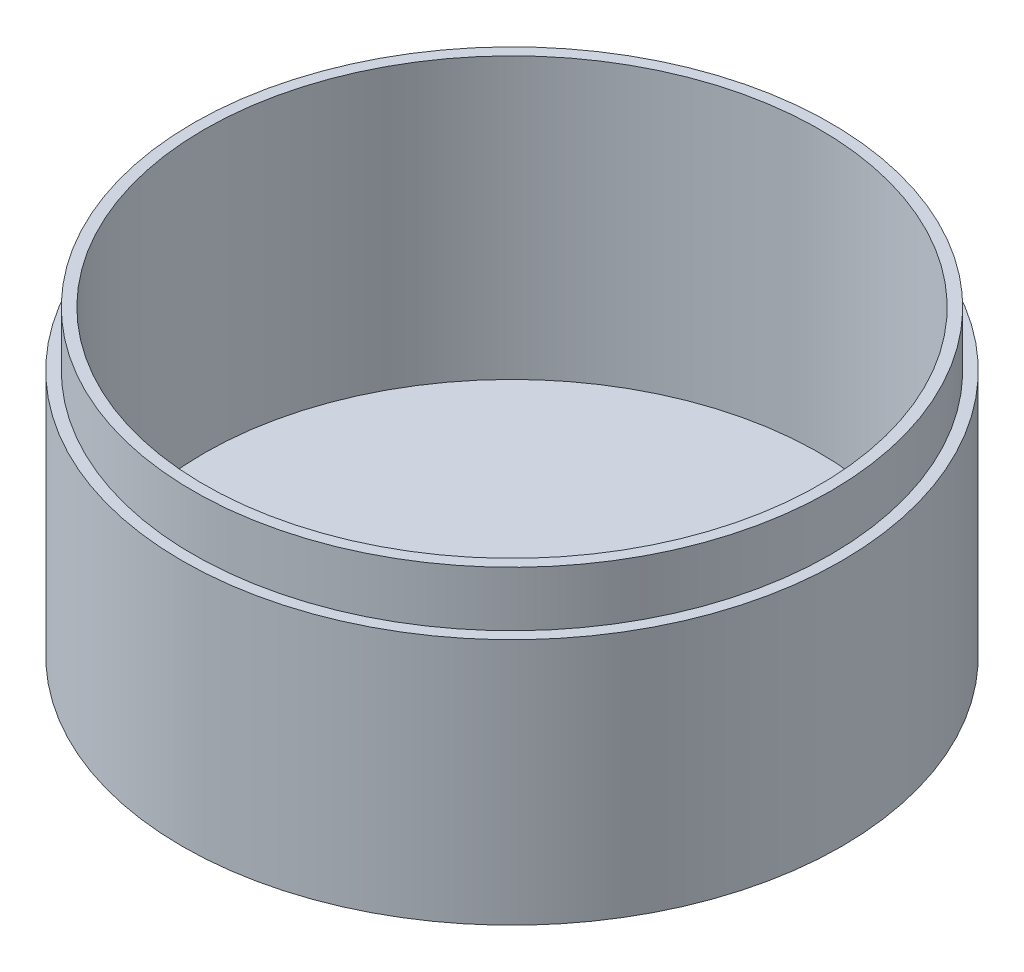
SolidWorks part; units mm, degrees
ref_plane "Front Plane" through (0, 0, 0) normal (0, 0, 1) x (1, 0, 0)
ref_plane "Top Plane" through (0, 0, 0) normal (0, 1, 0) x (1, 0, 0)
ref_plane "Right Plane" through (0, 0, 0) normal (1, 0, 0) x (0, 0, -1)
sketch "Sketch1" plane through (0, 0, 0) normal (0, 0, 1) x (1, 0, 0)
  line L0 (0, 0) -> (76.2, 0)
  line L1 (76.2, 0) -> (76.2, 57.15)
  line L2 (76.2, 57.15) -> (73.66, 57.15)
  line L3 (73.66, 57.15) -> (73.66, 69.85)
  line L4 (73.66, 69.85) -> (71.12, 69.85)
  line L5 (71.12, 69.85) -> (71.12, 5.08)
  line L6 (71.12, 5.08) -> (0, 5.08)
  line L7 (0, 5.08) -> (0, 0)
  line L8 (0, 5.08) -> (0, 63.5914) construction
  dimension "D1" = 2.54
  dimension "D2" = 5.08
  dimension "D3" = 5.08
  dimension "D4" = 69.85
  dimension "D5" = 12.7
  dimension "D6" = 152.4
revolve "Revolve1" add sketch "Sketch1" angle 360 about L7
